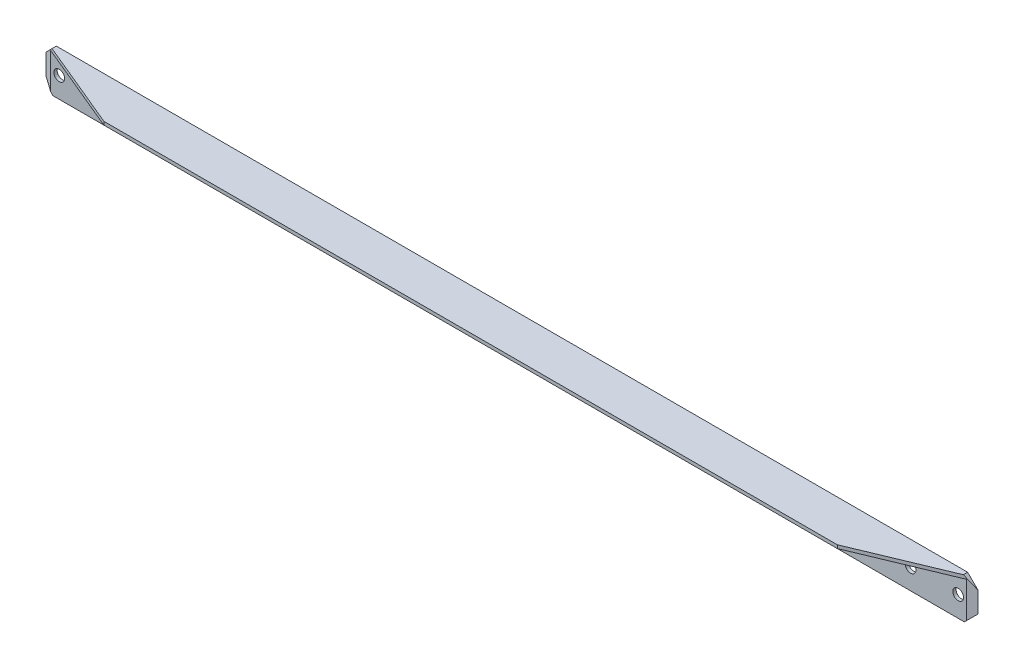
SolidWorks part; units mm, degrees
ref_plane "前视基准面" through (0, 0, 0) normal (0, 0, 1) x (1, 0, 0)
ref_plane "上视基准面" through (0, 0, 0) normal (0, 1, 0) x (1, 0, 0)
ref_plane "右视基准面" through (0, 0, 0) normal (1, 0, 0) x (0, 0, -1)
sketch "草图1" plane through (0, 0, 0) normal (0, 0, 1) x (1, 0, 0)
  line L0 (-1000, 0) -> (49000, 0) construction
  line L1 (-1126, 0) -> (1126, 0)
  line L2 (1126, 0) -> (1126, 100)
  line L3 (1126, 100) -> (-1126, 100)
  line L4 (-531.6366, 50) -> (49468.3634, 50) construction
  line L5 (1086, 100) -> (1086, 0) construction
  line L6 (971, 100) -> (971, 0) construction
  line L7 (0, 100) -> (0, 0.8753) construction
  line L8 (80, 100) -> (80, 0) construction
  line L9 (160, 100) -> (160, 0) construction
  line L10 (-1126, 0) -> (-1126, 100)
  circle A0 centre (1086, 50) radius 13
  circle A1 centre (971, 50) radius 13
  circle A2 centre (0, 50) radius 13
  circle A3 centre (80, 50) radius 13
  circle A4 centre (160, 50) radius 13
  circle A5 centre (-80, 50) radius 13
  circle A6 centre (-160, 50) radius 13
  circle A7 centre (-971, 50) radius 13
  circle A8 centre (-1086, 50) radius 13
  point P11 (1086, 50)
  point P16 (971, 50)
  point P19 (0, 50)
  point P27 (80, 50)
  point P28 (160, 50)
  point P42 (0, 0)
  dimension "D6" = 26
  dimension "D7" = 115
  dimension "D8" = 26
  dimension "D9" = 26
  dimension "D12" = 26
  dimension "D13" = 26
  dimension "D1" = 1126
  dimension "D2" = 100
  dimension "D4" = 50
  dimension "D5" = 40
  dimension "D10" = 80
  dimension "D11" = 80
extrude "凸台-拉伸1" add sketch "草图1" along normal blind 8
sketch "草图2" plane through (0, 0, 8) normal (0, 0, 1) x (1, 0, 0)
  line L1 (-1126, 100) -> (1126, 100)
  line L2 (-1126, 100) -> (-1126, 92)
  line L3 (-1126, 92) -> (1126, 92)
  line L4 (1126, 100) -> (1126, 92)
  point P0 (-1126, 100)
  dimension "D1" = 2252
  dimension "D2" = 8
extrude "凸台-拉伸2" add sketch "草图2" along normal blind 92
sketch "草图3" plane through (0, 100, 0) normal (0, 1, 0) x (1, 0, 0)
  line L0 (886, 0) -> (886, -100) construction
  line L1 (1126, 0) -> (-1126, 0) construction
  line L2 (1126, -100) -> (-1126, -100) construction
  line L3 (1126, -100) -> (1126, 0) construction
  line L4 (886, -100) -> (1126, 0)
  line L5 (1126, 0) -> (1126, -100)
  line L6 (1126, -100) -> (886, -100)
  point P8 (1126, 0)
  dimension "D1" = 240
chamfer "倒角3" distance 25 distance2 25 1 edges at (1126, 0, 4)
chamfer "倒角4" distance 25 distance2 25 1 edges at (1126, 100, 50)
extrude "切除-拉伸3" cut sketch "草图3" against normal through all
chamfer "倒角5" distance 25 distance2 25 1 edges at (-1126, 0, 4)
chamfer "倒角6" distance 25 distance2 25 1 edges at (-1126, 100, 50)
mirror "镜向8" about plane through (0, 0, 0) normal (1, 0, 0) of "切除-拉伸3"
